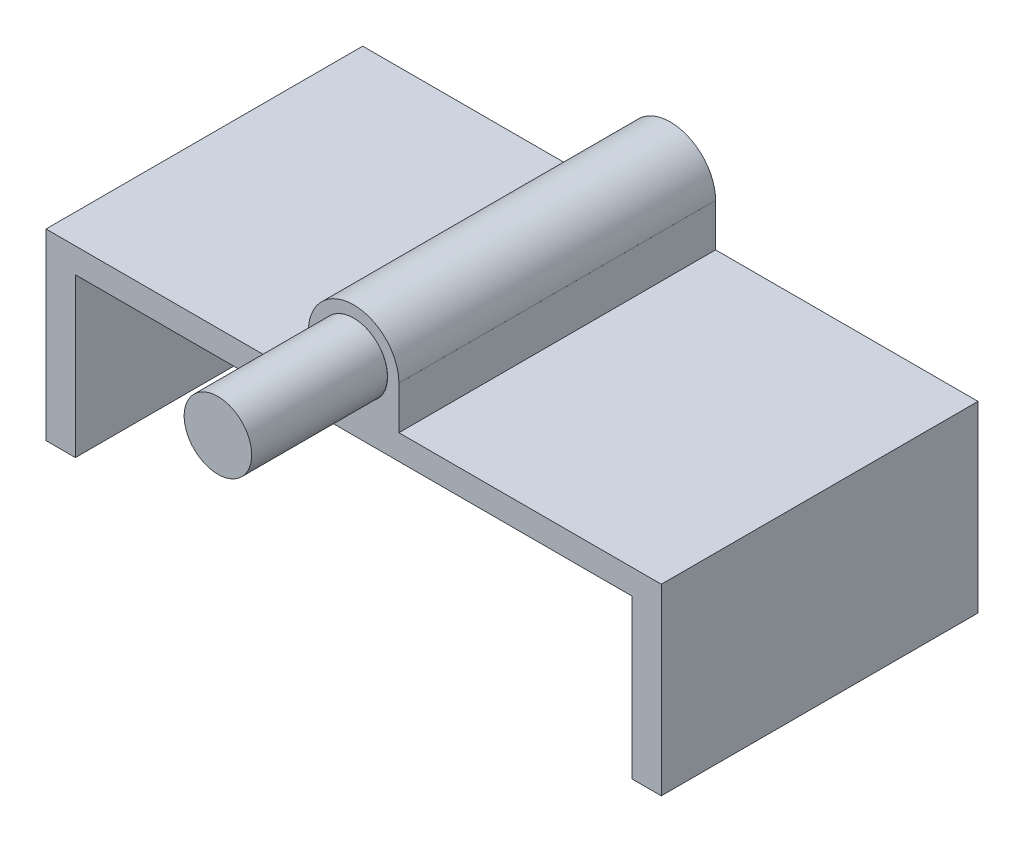
SolidWorks part; units mm, degrees
ref_plane "Front Plane" through (0, 0, 0) normal (0, 0, 1) x (1, 0, 0)
ref_plane "Top Plane" through (0, 0, 0) normal (0, 1, 0) x (1, 0, 0)
ref_plane "Right Plane" through (0, 0, 0) normal (1, 0, 0) x (0, 0, -1)
sketch "Sketch1" plane through (0, 0, 0) normal (0, 0, 1) x (1, 0, 0)
  line L1 (0, 0) -> (14, 0)
  line L2 (0, 0) -> (0, 5)
  line L3 (0, 5) -> (14, 5)
  line L4 (14, 0) -> (14, 5)
  dimension "D1" = 14
  dimension "D2" = 5
extrude "Boss-Extrude1" add sketch "Sketch1" along normal blind 7
sketch "Sketch2" plane through (0, 5, 0) normal (0, 1, 0) x (1, 0, 0)
  line L0 (0, 0) -> (6, 0) construction
  line L1 (14, 0) -> (0, 0) construction
  line L2 (14, 0) -> (8, 0) construction
  dimension "D1" = 6
  dimension "D2" = 2
sketch "Sketch7" plane through (0, 0, 7) normal (0, 0, 1) x (1, 0, 0)
  line L0 (0, 0) -> (1, 0) construction
  line L1 (0, 0) -> (14, 0) construction
  line L2 (14, 0) -> (13, 0) construction
  line L4 (1, 0) -> (13, 0)
  line L5 (1, 0) -> (1, 3.5)
  line L6 (1, 3.5) -> (13, 3.5)
  line L7 (13, 0) -> (13, 3.5)
  dimension "D1" = 3.5
extrude "Cut-Extrude1" cut sketch "Sketch7" against normal through all
sketch "Sketch8" plane through (0, 0, 7) normal (0, 0, 1) x (1, 0, 0)
  line L0 (14, 0) -> (14, 5) construction
  line L1 (0, 5) -> (14, 5)
  line L2 (0, 5) -> (0, 4.0515)
  line L3 (0, 4.0515) -> (14, 4.0515)
  line L4 (14, 5) -> (14, 4.0515)
extrude "Cut-Extrude2" cut sketch "Sketch8" against normal up to surface (7 mm away) up to face at (7, 2.125, 0)
sketch "Sketch20" plane through (0, 0, 7) normal (0, 0, 1) x (1, 0, 0)
  line L0 (0, 4.0515) -> (14, 4.0515) construction
  line L1 (6, 4.0515) -> (8, 4.0515)
  line L2 (6, 4.0515) -> (6, 5)
  line L3 (6, 5) -> (8, 5)
  line L4 (8, 4.0515) -> (8, 5)
  line L5 (14, 5) -> (8, 5) construction
extrude "Boss-Extrude9" add sketch "Sketch20" against normal up to surface (7 mm away) up to face at (7, 1.8879, 0)
sketch "Sketch21" plane through (0, 0, 7) normal (0, 0, 1) x (1, 0, 0)
  line L0 (8, 5) -> (6, 5) construction
  circle A0 centre (7, 5) radius 0.9997
extrude "Boss-Extrude10" add sketch "Sketch21" against normal up to surface (7 mm away) up to face at (7, 2.7672, 0)
sketch "Sketch22" plane through (0, 0, 7) normal (0, 0, 1) x (1, 0, 0)
  circle A0 centre (7, 4.9962) radius 0.75
extrude "Cut-Extrude3" cut sketch "Sketch22" against normal up to surface (7 mm away) up to face at (7, 3.1575, 0)
sketch "Sketch23" plane through (0, 0, 0) normal (-1, 0, 0) x (0, 0, 1)
  line L1 (0, 4.0515) -> (7, 4.0515)
  line L2 (0, 4.0515) -> (0, 0)
  line L3 (0, 0) -> (7, 0)
  line L4 (7, 4.0515) -> (7, 0)
extrude "Cut-Extrude4" cut sketch "Sketch23" against normal blind 0.4
sketch "Sketch24" plane through (14, 0, 0) normal (1, 0, 0) x (0, 0, -1)
  line L1 (-7, 4.0515) -> (0, 4.0515)
  line L2 (-7, 4.0515) -> (-7, 0)
  line L3 (-7, 0) -> (0, 0)
  line L4 (0, 4.0515) -> (0, 0)
extrude "Cut-Extrude5" cut sketch "Sketch24" against normal blind 0.4
sketch "Sketch25" plane through (0.4, 0, 0) normal (-1, 0, 0) x (0, 0, 1)
  line L1 (0, 4.0515) -> (7, 4.0515)
  line L2 (0, 4.0515) -> (0, 0)
  line L3 (0, 0) -> (7, 0)
  line L4 (7, 4.0515) -> (7, 0)
sketch "Sketch26" plane through (13.6, 0, 0) normal (1, 0, 0) x (0, 0, -1)
  line L1 (-7, 4.0515) -> (0, 4.0515)
  line L2 (-7, 4.0515) -> (-7, 0)
  line L3 (-7, 0) -> (0, 0)
  line L4 (0, 4.0515) -> (0, 0)
extrude "Boss-Extrude13" add sketch "Sketch25" along normal blind 0.2
extrude "Boss-Extrude14" add sketch "Sketch26" along normal blind 0.2
sketch "Sketch29" plane through (1, 0, 0) normal (1, 0, 0) x (0, 0, -1)
  line L1 (0, 3.5) -> (-7, 3.5)
  line L2 (0, 3.5) -> (0, 0)
  line L3 (0, 0) -> (-7, 0)
  line L4 (-7, 3.5) -> (-7, 0)
extrude "Cut-Extrude8" cut sketch "Sketch29" against normal blind 0.15
sketch "Sketch30" plane through (13, 0, 0) normal (-1, 0, 0) x (0, 0, 1)
  line L1 (0, 3.5) -> (7, 3.5)
  line L2 (0, 3.5) -> (0, 0)
  line L3 (0, 0) -> (7, 0)
  line L4 (7, 3.5) -> (7, 0)
extrude "Cut-Extrude9" cut sketch "Sketch30" against normal blind 0.15
sketch "Sketch31" plane through (0, 0, 7) normal (0, 0, 1) x (1, 0, 0)
  circle A0 centre (7, 5) radius 0.7462
extrude "Boss-Extrude15" add sketch "Sketch31" along normal blind 3 separate body
